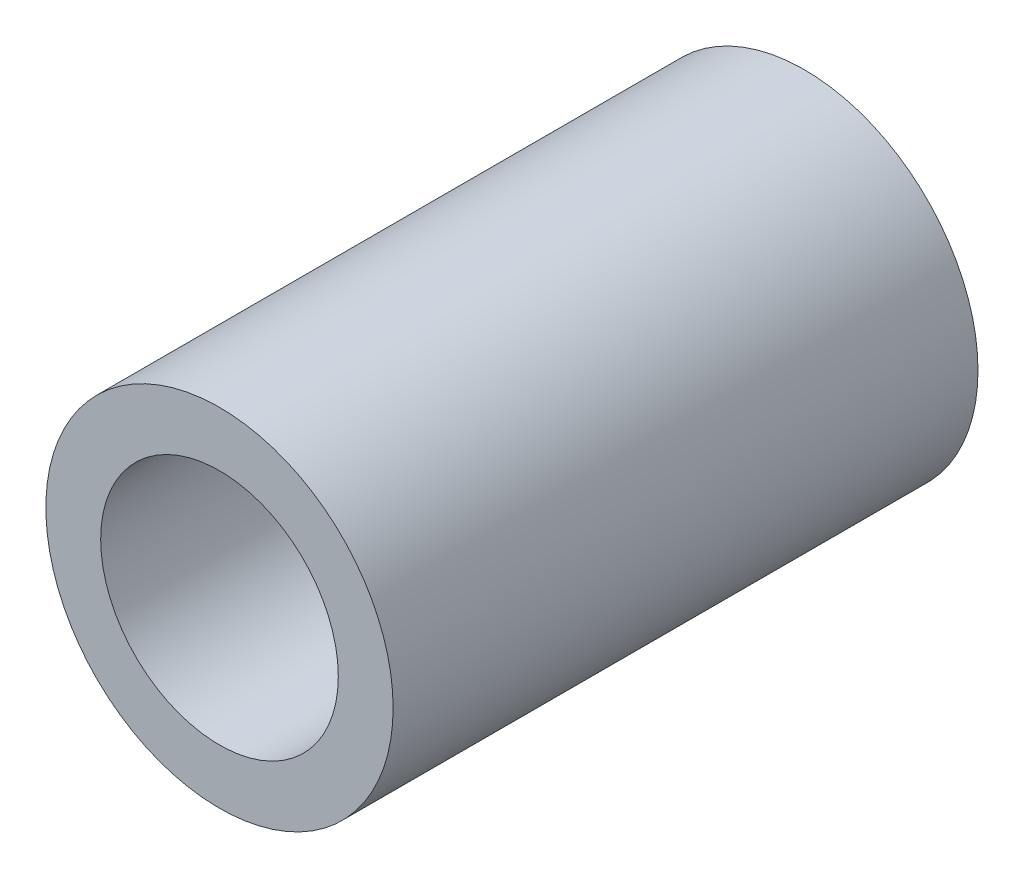
SolidWorks part; units mm, degrees
ref_plane "Plan de face" through (0, 0, 0) normal (0, 0, 1) x (1, 0, 0)
ref_plane "Plan de dessus" through (0, 0, 0) normal (0, 1, 0) x (1, 0, 0)
ref_plane "Plan de droite" through (0, 0, 0) normal (1, 0, 0) x (0, 0, -1)
sketch "Sketch1" plane through (0, 0, 0) normal (0, 0, 1) x (1, 0, 0)
  circle A0 centre (0, 0) radius 4.75
  circle A1 centre (0, 0) radius 3.25
  point P4 (0, 0)
  dimension "D1" = 9.5
  dimension "D2" = 6.5
extrude "Boss-Extrude1" add sketch "Sketch1" along normal blind 16
cosmetic thread "Cosmetic Thread1" parameters "D2"=8
